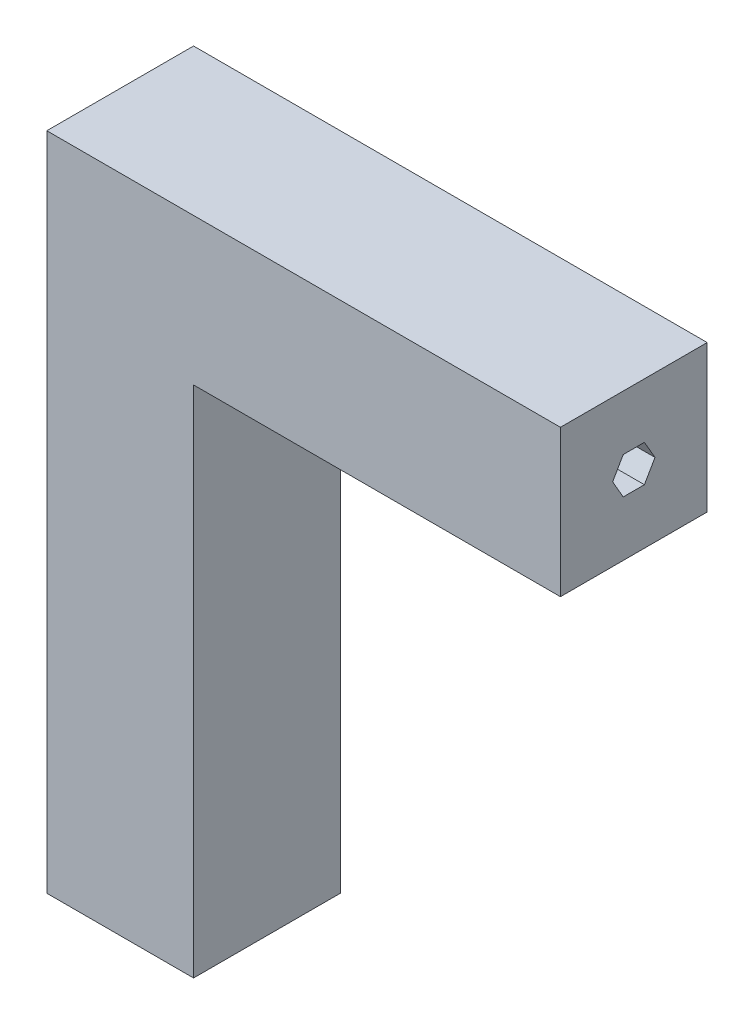
SolidWorks part; units mm, degrees
ref_plane "Front Plane" through (0, 0, 0) normal (0, 0, 1) x (1, 0, 0)
ref_plane "Top Plane" through (0, 0, 0) normal (0, 1, 0) x (1, 0, 0)
ref_plane "Right Plane" through (0, 0, 0) normal (1, 0, 0) x (0, 0, -1)
sketch "Sketch2" plane through (0, 0, 0) normal (0, 0, 1) x (1, 0, 0)
  line L1 (0, 0) -> (50.8, 0)
  line L2 (0, 0) -> (0, 228.6)
  line L3 (0, 228.6) -> (50.8, 228.6)
  line L4 (50.8, 0) -> (50.8, 177.8)
  line L5 (50.8, 228.6) -> (177.8, 228.6)
  line L7 (50.8, 177.8) -> (177.8, 177.8)
  line L8 (177.8, 228.6) -> (177.8, 177.8)
  dimension "D1" = 228.6
  dimension "D2" = 50.8
  dimension "D3" = 50.8
  dimension "D4" = 177.8
extrude "Boss-Extrude1" add sketch "Sketch2" against normal mid plane 50.8
sketch "Sketch3" plane through (177.8, 0, 0) normal (1, 0, 0) x (0, 0, -1)
  line L0 (25.4, 177.8) -> (25.4, 228.6) construction
  line L1 (7.3323, 203.2) -> (3.6662, 209.55)
  line L2 (3.6662, 209.55) -> (-3.6662, 209.55)
  line L3 (-3.6662, 209.55) -> (-7.3323, 203.2)
  line L4 (-7.3323, 203.2) -> (-3.6662, 196.85)
  line L5 (-3.6662, 196.85) -> (3.6662, 196.85)
  line L6 (3.6662, 196.85) -> (7.3323, 203.2)
  line L7 (25.4, 228.6) -> (-25.4, 228.6) construction
  circle A0 centre (0, 203.2) radius 6.35 construction
  dimension "D1" = 12.7
  dimension "D2" = 25.4
  dimension "D3" = 25.4
extrude "Cut-Extrude1" cut sketch "Sketch3" against normal blind 76.2
